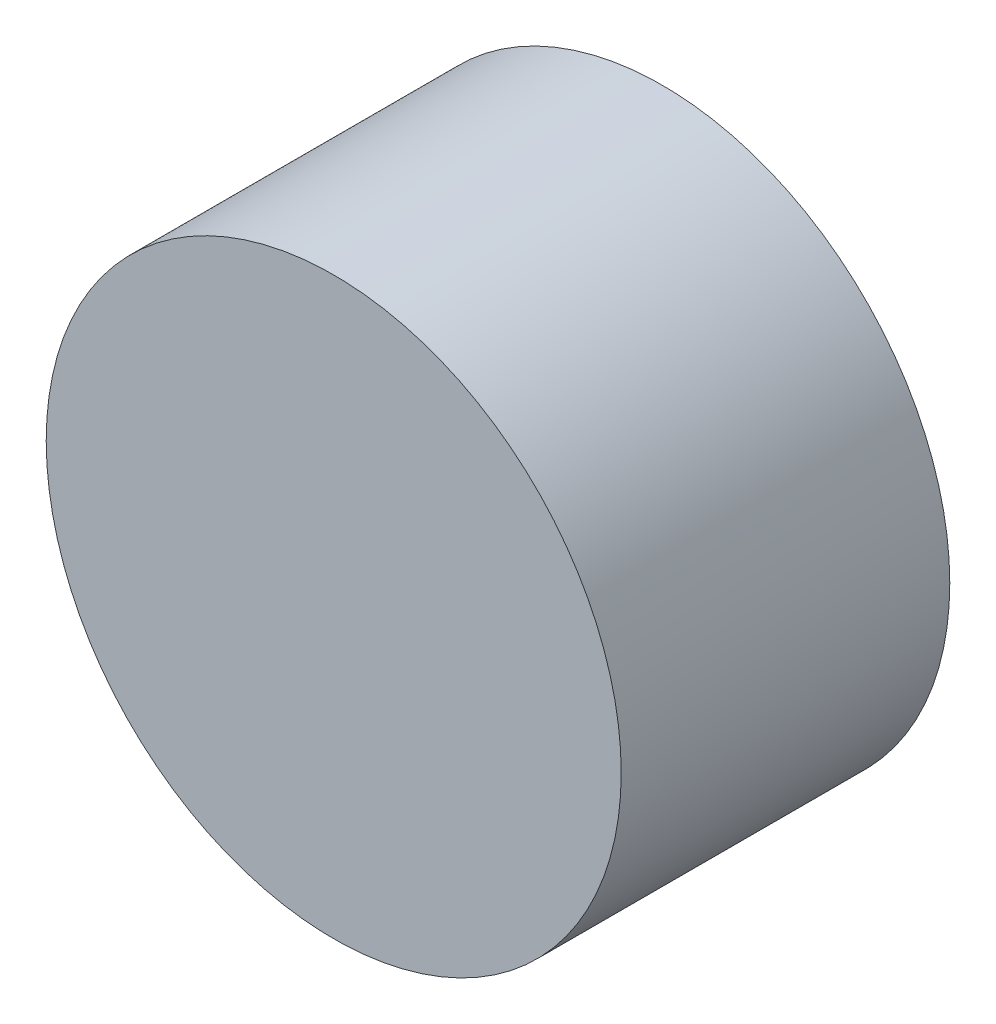
SolidWorks part; units mm, degrees
ref_plane "前视基准面" through (0, 0, 0) normal (0, 0, 1) x (1, 0, 0)
ref_plane "上视基准面" through (0, 0, 0) normal (0, 1, 0) x (1, 0, 0)
ref_plane "右视基准面" through (0, 0, 0) normal (1, 0, 0) x (0, 0, -1)
sketch "草图2" plane through (0, 0, 0) normal (0, 0, 1) x (1, 0, 0)
  circle A0 centre (0, 0) radius 14
  dimension "D1" = 28
extrude "凸台-拉伸1" add sketch "草图2" along normal blind 16
sketch "草图3" plane through (0, 0, 0) normal (0, 0, -1) x (-1, 0, 0)
  circle A0 centre (0, 0) radius 9.5
  dimension "D1" = 19
extrude "切除-拉伸1" cut sketch "草图3" against normal blind 8
sketch "草图4" plane through (0, 0, 0) normal (0, 0, -1) x (-1, 0, 0)
  circle A0 centre (0, 0) radius 9.51
extrude "切除-拉伸3" cut sketch "草图4" against normal blind 8
